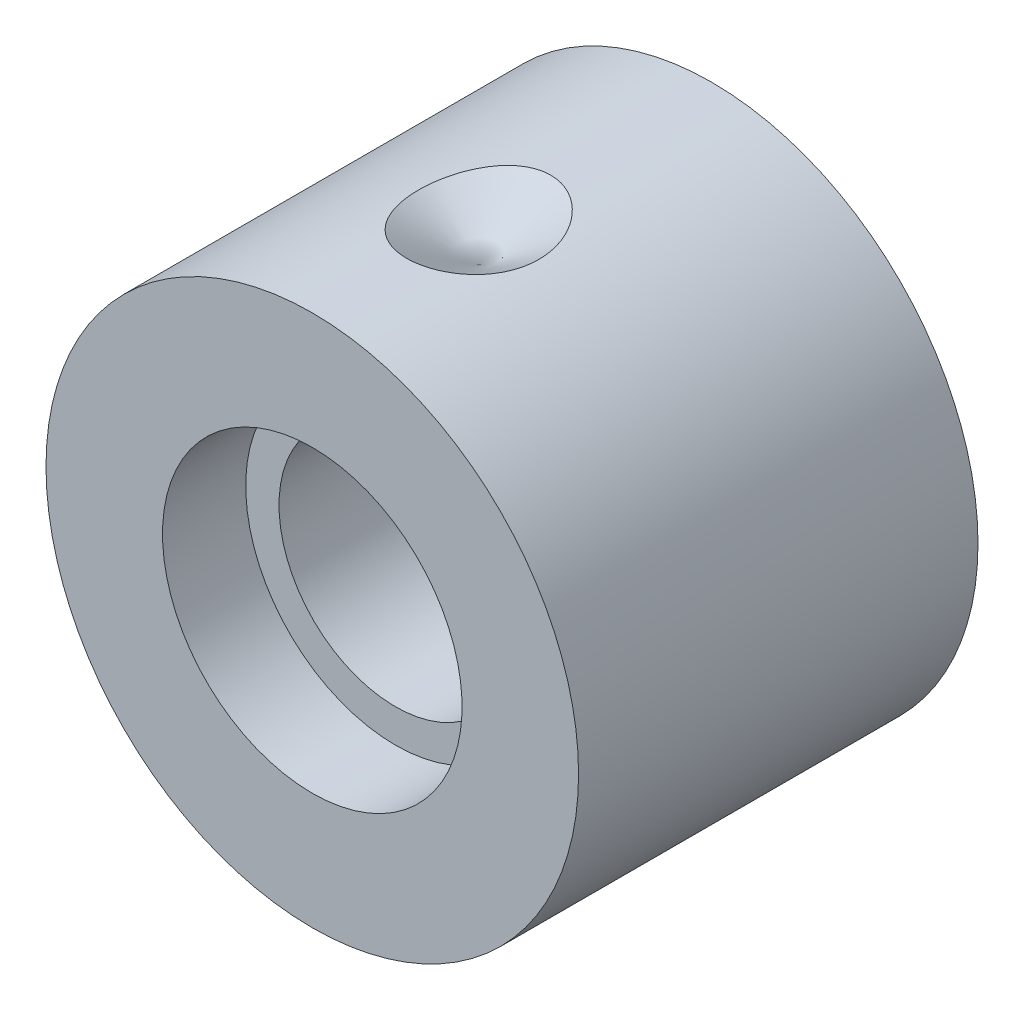
SolidWorks part; units mm, degrees
ref_plane "前基準面" through (0, 0, 0) normal (0, 0, 1) x (1, 0, 0)
ref_plane "上基準面" through (0, 0, 0) normal (0, 1, 0) x (1, 0, 0)
ref_plane "右基準面" through (0, 0, 0) normal (1, 0, 0) x (0, 0, -1)
sketch "草圖1" plane through (0, 0, 0) normal (1, 0, 0) x (0, 0, -1)
  line L0 (5, 0) -> (5, 9)
  line L1 (5, 9) -> (0, 9)
  line L2 (0, 9) -> (0, 16)
  line L3 (0, 16) -> (24, 16)
  line L4 (24, 16) -> (24, 0)
  line L5 (24, 0) -> (5, 0)
  dimension "D1" = 16
  dimension "D2" = 9
  dimension "D3" = 5
  dimension "D4" = 24
revolve "旋轉1" add sketch "草圖1" angle 360 about L5
sketch "草圖2" plane through (0, 0, 0) normal (1, 0, 0) x (0, 0, -1)
  line L0 (10, 11.1877) -> (10, 22.7778) construction
  line L1 (3.7183, 19.3245) -> (10, 19.3245)
  line L2 (3.7183, 17.1267) -> (10, 13.5)
  line L3 (0, 16) -> (0, -16) construction
  line L5 (10, 13.5) -> (10, 19.3245)
  line L6 (24, 16) -> (0, 16) construction
  line L7 (3.7183, 17.1267) -> (3.7183, 19.3245)
  dimension "D1" = 10
  dimension "D2" = 2.5
  dimension "D3" = 60
revolve "除料-旋轉1" cut sketch "草圖2" angle 360 about L0
hole_wizard "M16 螺紋孔1" positions "草圖4" profile "草圖3" tap size "M16" standard "ISO" end condition up to next
sketch "草圖4" plane through (0, 0, -5) normal (0, 0, 1) x (1, 0, 0)
  point P0 (0, 0)
sketch "草圖3" plane through (0, 0, -5) normal (1, 0, 0) x (0, -1, 0)
  line L0 (0, 0) -> (0, 19)
  line L1 (0, 19) -> (7, 19)
  line L2 (7, 19) -> (7, 0)
  line L5 (7, 0) -> (0, 0)
  line L11 (0, -6.35) -> (0, 107.95) construction
  dimension "貫穿螺孔鑽直徑" = 14
  dimension "貫穿螺孔鑽深度" = 19
cosmetic thread "鑽孔螺紋1" parameters "D2"=16
sketch "草圖6" plane through (0, 0, 0) normal (1, 0, 0) x (0, 0, -1)
  line L0 (10, 13.5) -> (14.3301, 16) construction
  line L1 (10, 13.5) -> (14.3301, 16)
